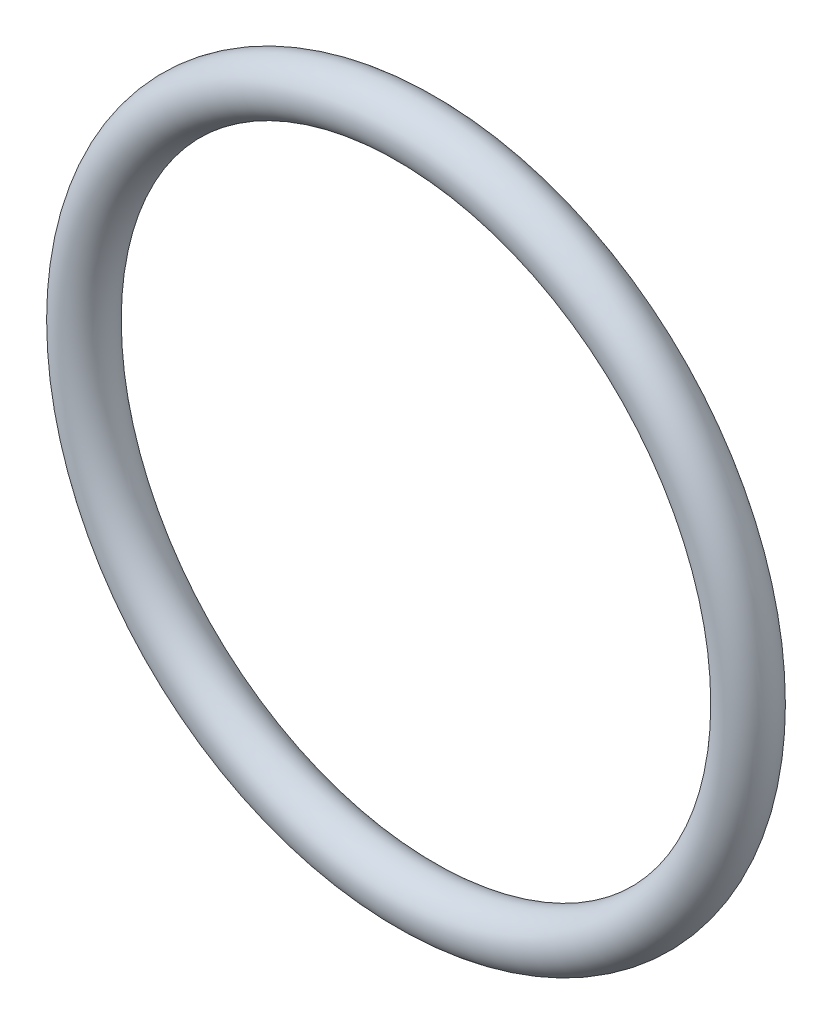
SolidWorks part; units mm, degrees
ref_plane "Front" through (0, 0, 0) normal (0, 0, 1) x (1, 0, 0)
ref_plane "Top" through (0, 0, 0) normal (0, 1, 0) x (1, 0, 0)
ref_plane "Right" through (0, 0, 0) normal (1, 0, 0) x (0, 0, -1)
sketch "Sketch1" plane through (0, 0, 0) normal (1, 0, 0) x (0, -1, 0)
  line L0 (0, -1.7653) -> (0, 1.7653) construction
  line L2 (-26.3614, 0) -> (26.3614, 0) construction
  line L3 (-20.4343, 0) -> (20.4343, 0) construction
  circle A0 centre (22.1996, 0) radius 1.7653
  point P9 (20.4343, 0)
  point P10 (23.9649, 0)
  point P13 (22.1996, 1.7653)
  point P14 (22.1996, -1.7653)
  dimension "Width" = 3.5306
  dimension "ID" = 40.8686
revolve "Revolve1" add sketch "Sketch1" angle 360 about L0
